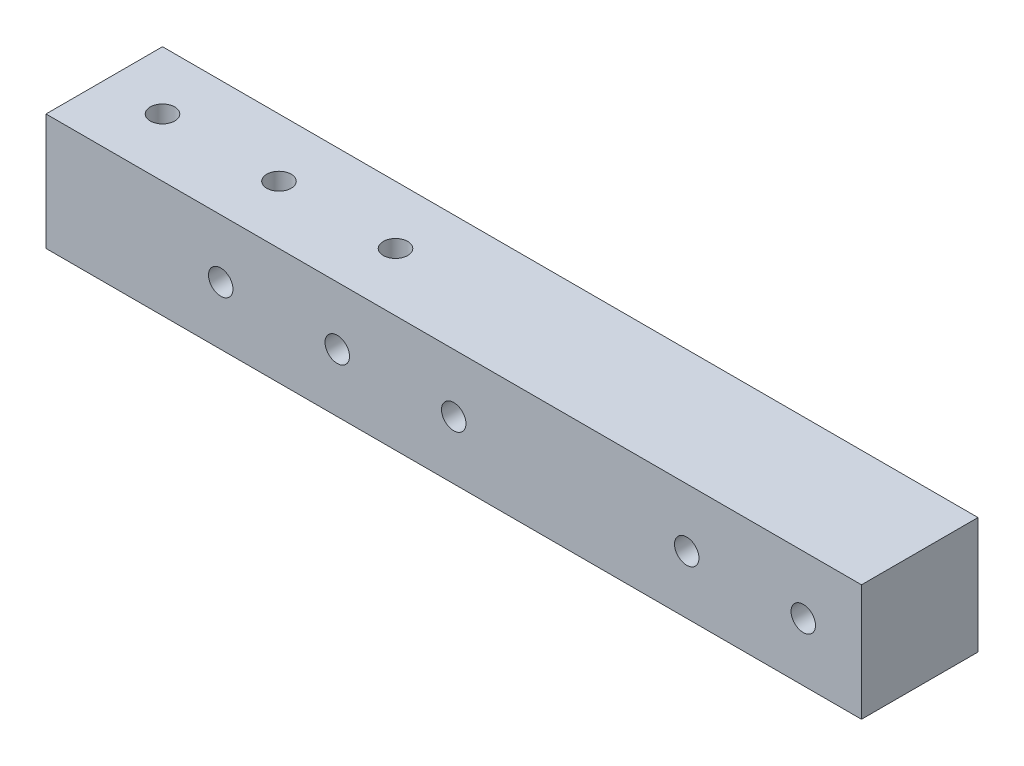
SolidWorks part; units mm, degrees
ref_plane "前视基准面" through (0, 0, 0) normal (0, 0, 1) x (1, 0, 0)
ref_plane "上视基准面" through (0, 0, 0) normal (0, 1, 0) x (1, 0, 0)
ref_plane "右视基准面" through (0, 0, 0) normal (1, 0, 0) x (0, 0, -1)
sketch "草图1" plane through (0, 0, 0) normal (1, 0, 0) x (0, 0, -1)
  line L1 (-10, 10) -> (10, 10)
  line L2 (-10, 10) -> (-10, -10)
  line L3 (-10, -10) -> (10, -10)
  line L4 (10, 10) -> (10, -10)
  line L5 (-10, 10) -> (10, -10) construction
  line L6 (-10, -10) -> (10, 10) construction
  point P0 (0, 0)
  dimension "D1" = 20
  dimension "D2" = 20
extrude "凸台-拉伸1" add sketch "草图1" along normal blind 140
sketch "草图2" plane through (0, 10, 0) normal (0, 1, 0) x (1, 0, 0)
  line L0 (140, 10) -> (0, 10) construction
  line L1 (0, 10) -> (0, -10) construction
  circle A0 centre (10, 0) radius 2.1
  circle A1 centre (30, 0) radius 2.1
  circle A2 centre (50, 0) radius 2.1
  dimension "D1" = 10
  dimension "D3" = 4.2
  dimension "D2" = 10
  dimension "D5" = 20
  dimension "D4" = 3
sketch "草图3" plane through (0, 0, 10) normal (0, 0, 1) x (1, 0, 0)
  line L0 (140, 10) -> (0, 10) construction
  line L1 (140, 10) -> (140, -10) construction
  circle A0 centre (30, 0) radius 2.1
  circle A1 centre (50, 0) radius 2.1
  circle A2 centre (70, 0) radius 2.1
  circle A3 centre (130, 0) radius 2.1
  circle A4 centre (110, 0) radius 2.1
  point P17 (114.8325, 0.5983)
  dimension "D1" = 4.2
  dimension "D6" = 30
  dimension "D8" = 4.2
  dimension "D9" = 4.2
  dimension "D10" = 4.2
  dimension "D2" = 10
  dimension "D3" = 30
  dimension "D5" = 20
  dimension "D7" = 10
  dimension "D11" = 10
  dimension "D4" = 3
extrude "切除-拉伸1" cut sketch "草图3" against normal through all
extrude "切除-拉伸2" cut sketch "草图2" against normal through all
